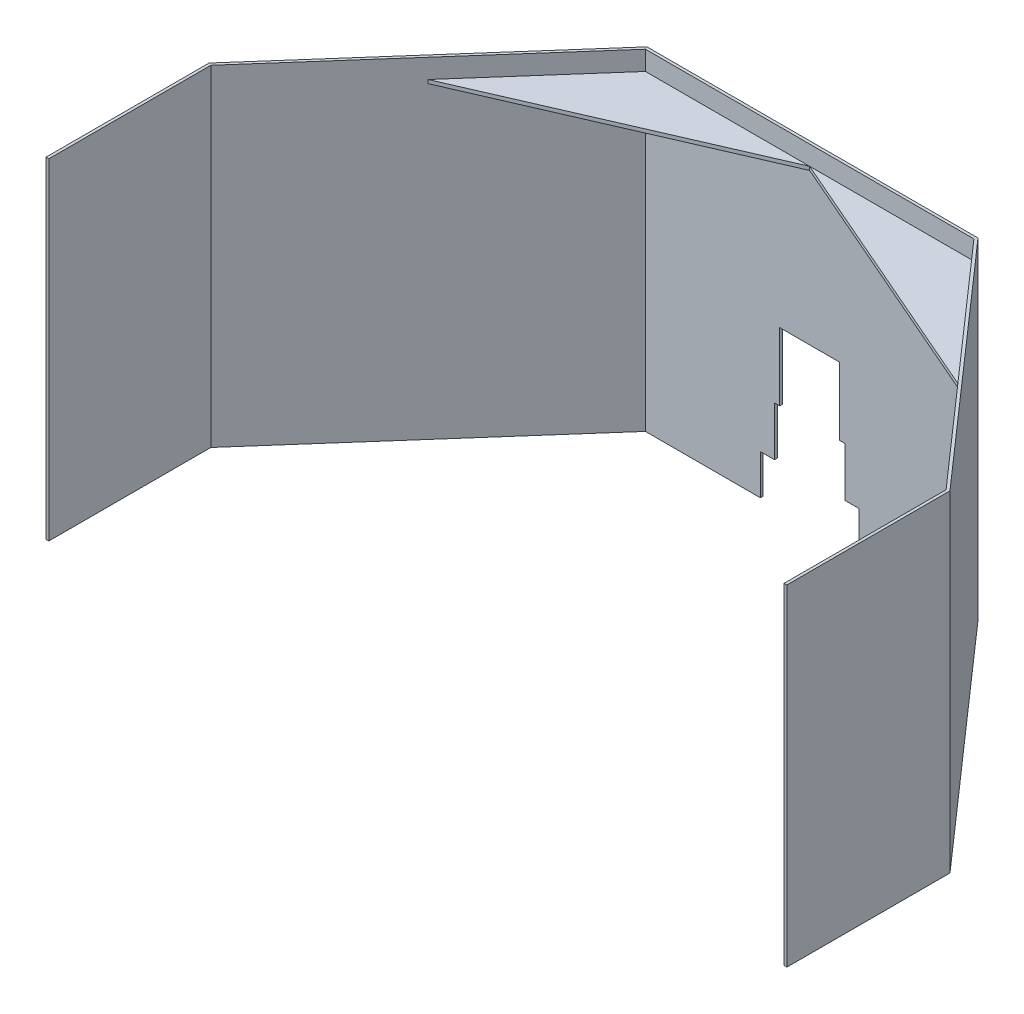
SolidWorks part; units mm, degrees
ref_plane "Front Plane" through (0, 0, 0) normal (0, 0, 1) x (1, 0, 0)
ref_plane "Top Plane" through (0, 0, 0) normal (0, 1, 0) x (1, 0, 0)
ref_plane "Right Plane" through (0, 0, 0) normal (1, 0, 0) x (0, 0, -1)
sketch "Sketch1" plane through (0, 0, 0) normal (0, 1, 0) x (1, 0, 0)
  line L0 (-117.5045, 326.1556) -> (117.5045, 326.1556)
  line L3 (-81.7739, 326.1556) -> (86.8843, 326.1556)
  line L4 (-81.7739, 326.1556) -> (-81.7739, 382.1556) construction
  line L5 (-81.7739, 382.1556) -> (86.8843, 382.1556) construction
  line L6 (86.8843, 326.1556) -> (86.8843, 382.1556) construction
  line L9 (-117.5045, 326.1556) -> (-263, 160.7545)
  line L10 (-263, 160.7545) -> (-263, 45.0012)
  line L11 (-263, 45.0012) -> (-261, 45.0012)
  line L12 (-116.6001, 324.1556) -> (116.6001, 324.1556)
  line L15 (-116.6001, 324.1556) -> (-261, 160)
  line L16 (-261, 160) -> (-261, 45.0012)
  line L17 (116.6001, 324.1556) -> (261, 160)
  line L18 (261, 160) -> (261, 45.0035)
  line L19 (261, 45.0035) -> (263, 45.0035)
  line L20 (263, 45.0035) -> (263, 160.7545)
  line L21 (263, 160.7545) -> (117.5045, 326.1556)
  dimension "D1" = 56
  dimension "D2" = 2
extrude "Boss-Extrude5" add sketch "Sketch1" along normal blind 235 contours L18 L19 L20 L21 L0 L9 L10 L11 L16 L15 L12 L17
sketch "Sketch4" plane through (0, 0, -326.1556) normal (0, 0, -1) x (-1, 0, 0)
  line L0 (0, 0) -> (0, 111.5) construction
  line L1 (-117.5045, 235) -> (-117.5045, 0) construction
  line L2 (117.5045, 235) -> (117.5045, 0) construction
  line L3 (-117.5045, 28.4) -> (117.5045, 28.4) construction
  line L4 (154.6349, 0) -> (-154.6349, 0) construction
  line L5 (-117.5045, 63.4) -> (117.5045, 63.4) construction
  line L6 (-117.5045, 111.5) -> (117.5045, 111.5) construction
  line L7 (-35, 28.4) -> (35, 28.4)
  line L8 (-35, 28.4) -> (-35, 0)
  line L9 (-35, 0) -> (35, 0)
  line L10 (35, 28.4) -> (35, 0)
  line L11 (-35, 28.4) -> (35, 0) construction
  line L12 (-35, 0) -> (35, 28.4) construction
  line L14 (-25, 63.4) -> (25, 63.4)
  line L15 (-25, 63.4) -> (-25, 28.4)
  line L16 (-25, 28.4) -> (25, 28.4)
  line L17 (25, 63.4) -> (25, 28.4)
  line L18 (-25, 63.4) -> (25, 28.4) construction
  line L19 (-25, 28.4) -> (25, 63.4) construction
  line L20 (-21.25, 111.5) -> (21.25, 111.5)
  line L21 (-21.25, 111.5) -> (-21.25, 63.4)
  line L22 (-21.25, 63.4) -> (21.25, 63.4)
  line L23 (21.25, 111.5) -> (21.25, 63.4)
  line L24 (-21.25, 111.5) -> (21.25, 63.4) construction
  line L25 (-21.25, 63.4) -> (21.25, 111.5) construction
  point P0 (0, 14.2)
  point P20 (0, 45.9)
  point P25 (0, 87.45)
  line M2 (-117.5045, 0) -> (117.5045, 0)
  dimension "D1" = 28.4
  dimension "D2" = 63.4
  dimension "D3" = 83.1
  dimension "D4" = 70
  dimension "D5" = 50
  dimension "D6" = 42.5
extrude "Cut-Extrude1" cut sketch "Sketch4" against normal up to surface (2 mm away) contours L23 L20 L21 L14 | L17 L14 L15 L7 | L10 L7 L8 M2 up to face at (0, 117.5, -324.1556)
sketch "Sketch5" plane through (-226.4895, 0, -199.232) normal (0.7508, 0, 0.6605) x (0.6605, 0, -0.7508)
  line L0 (57.0636, 235) -> (57.0636, 0) construction
  line L1 (166.3778, 235) -> (-52.2506, 235) construction
  line L2 (166.3778, 0) -> (-52.2506, 0) construction
sketch "Sketch6" plane through (0, 0, -324.1556) normal (0, 0, 1) x (1, 0, 0)
  line L0 (0, 235) -> (0, 111.5) construction
  line L1 (-116.6001, 235) -> (116.6001, 235) construction
  line L2 (-21.25, 111.5) -> (21.25, 111.5) construction
  line L3 (-77.2442, 0) -> (-77.2442, 235) construction
  line L4 (154.6349, 0) -> (-154.6349, 0) construction
  line L5 (77.2442, 0) -> (77.2442, 235) construction
  dimension "D1" = 39.3559
  dimension "D2" = 39.3559
sketch "Sketch7" plane through (226.4895, 0, -199.232) normal (-0.7508, 0, 0.6605) x (0.6605, 0, 0.7508)
  line L0 (-57.0636, 235) -> (-57.0636, 0) construction
  line L1 (-166.3778, 235) -> (52.2506, 235) construction
  line L2 (-166.3778, 0) -> (52.2506, 0) construction
ref_plane "Plane1" through (-118.5217, 0, -272.6302) normal (0.3987, 0, 0.9171) x (0.9171, 0, -0.3987)
sketch "Sketch8" plane through (-118.5217, 0, -272.6302) normal (0.3987, 0, 0.9171) x (0.9171, 0, -0.3987)
  line L0 (-76.6322, 220.0332) -> (129.2372, 220.0332)
  line L1 (-76.6322, 235) -> (-76.6322, 0) construction
  line L2 (129.2372, 235) -> (129.2372, 111.5) construction
ref_plane "Plane2" through (118.5217, 0, -272.6302) normal (-0.3987, 0, 0.9171) x (0.9171, 0, 0.3987)
sketch "Sketch9" plane through (118.5217, 0, -272.6302) normal (-0.3987, 0, 0.9171) x (0.9171, 0, 0.3987)
  line L0 (-129.2372, 220.0332) -> (76.6322, 220.0332)
  line L1 (76.6322, 235) -> (76.6322, 0) construction
rib "Rib1" sketch "Sketch9" sketch "Sketch9" thickness 2.54 extrusion direction normal to sketch draft on no parameters "D1"=2.54
rib "Rib2" sketch "Sketch8" sketch "Sketch8" thickness 2.54 extrusion direction normal to sketch draft on no parameters "D1"=2.54
ref_plane "Plane3" through (-181.8645, 0, -247.1807) normal (0.5926, 0, 0.8055) x (0.8055, 0, -0.5926)
sketch "Sketch10" plane through (-181.8645, 0, -247.1807) normal (0.5926, 0, 0.8055) x (0.8055, 0, -0.5926)
  line L0 (-8.6105, 13.746) -> (129.8867, 13.746)
  line L1 (-8.6105, 235) -> (-8.6105, 0) construction
  line L2 (129.8867, 0) -> (129.8867, 235) construction
equation "\"gap\"= 1mm"
equation "\"casewidth\"= 2mm"
equation "\"D2@Sketch1\"=\"casewidth\""
equation "\"flatheight\"= 235mm"
equation "\"D1@Boss-Extrude5\"=\"flatheight\""
